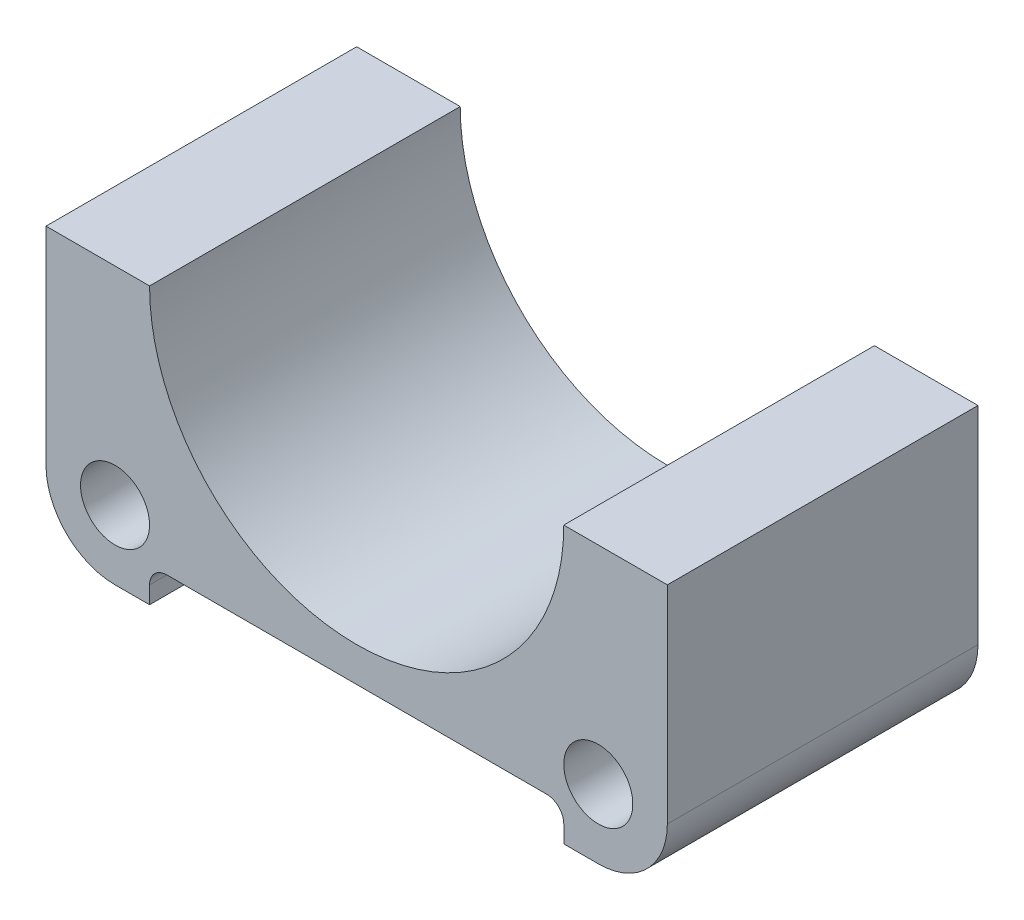
SolidWorks part; units mm, degrees
ref_plane "Front Plane" through (0, 0, 0) normal (0, 0, 1) x (1, 0, 0)
ref_plane "Top Plane" through (0, 0, 0) normal (0, 1, 0) x (1, 0, 0)
ref_plane "Right Plane" through (0, 0, 0) normal (1, 0, 0) x (0, 0, -1)
sketch "Sketch1" plane through (0, 0, 0) normal (0, 0, 1) x (1, 0, 0)
  line L0 (0, 0) -> (38744.4573, 0) construction
  line L1 (0, 0) -> (0, 38744.4573) construction
  line L2 (60, 40) -> (90, 40)
  line L3 (-70, -40) -> (-60, -40)
  line L4 (-90, -20) -> (-90, 40)
  line L5 (-90, 40) -> (-60, 40)
  line L6 (90, -20) -> (90, 40)
  line L7 (-90, -40) -> (90, 40) construction
  line L8 (-90, 40) -> (90, -40) construction
  line L9 (-60, -40) -> (-60, -35)
  line L10 (-55, -30) -> (55, -30)
  line L11 (60, -35) -> (60, -40)
  line L12 (60, -40) -> (70, -40)
  arc A0 (-60, 40) -> (60, 40) centre (0, 40) ccw
  arc A1 (70, -40) -> (90, -20) centre (70, -20) ccw
  arc A2 (-70, -40) -> (-90, -20) centre (-70, -20) cw
  circle A3 centre (-70, -20) radius 10
  circle A4 centre (70, -20) radius 10
  arc A5 (-60, -35) -> (-55, -30) centre (-55, -35) cw
  arc A6 (55, -30) -> (60, -35) centre (55, -35) cw
  point P5 (0, 0)
  point P28 (0, -30)
  point P30 (0, 0)
  dimension "D3" = 60
  dimension "D5" = 20
  dimension "D6" = 20
  dimension "D8" = 5
  dimension "D1" = 80
  dimension "D2" = 180
  dimension "D4" = 30
  dimension "D7" = 120
  dimension "D9" = 10
extrude "Boss-Extrude1" add sketch "Sketch1" along normal blind 90
